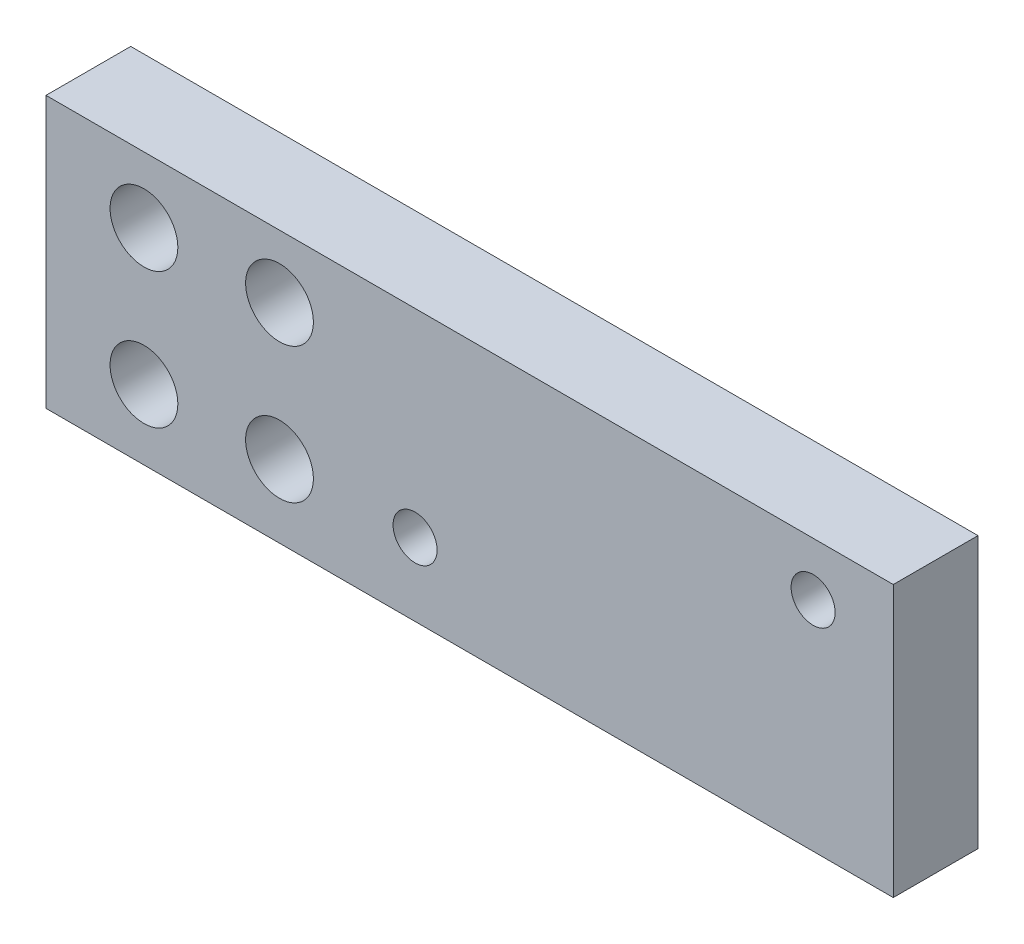
SolidWorks part; units mm, degrees
ref_plane "前基準面" through (0, 0, 0) normal (0, 0, 1) x (1, 0, 0)
ref_plane "上基準面" through (0, 0, 0) normal (0, 1, 0) x (1, 0, 0)
ref_plane "右基準面" through (0, 0, 0) normal (1, 0, 0) x (0, 0, -1)
sketch "草圖1" plane through (0, 0, 0) normal (0, 0, 1) x (1, 0, 0)
  line L5 (-22.7861, 3.8985) -> (27.2139, 3.8985)
  line L6 (-22.7861, 3.8985) -> (-22.7861, -12.1015)
  line L7 (-22.7861, -12.1015) -> (27.2139, -12.1015)
  line L8 (27.2139, 3.8985) -> (27.2139, -12.1015)
  line L9 (2.2139, -12.1015) -> (2.2139, 3.8985) construction
  line L10 (-22.7861, -4.1015) -> (27.2139, -4.1015) construction
  circle A4 centre (-17.006, 0.0173) radius 2
  circle A5 centre (-17.006, -7.9827) radius 2
  circle A6 centre (-9.006, 0.1915) radius 2
  circle A7 centre (-9.006, -7.8085) radius 2
  circle A8 centre (-1.006, -7.8085) radius 1.3
  circle A9 centre (22.4839, 0.7486) radius 1.3
  point P8 (10.6298, -0.8045)
  point P9 (0, 0)
  point P10 (23.9961, 1.2995)
  point P76 (2.2139, -4.1015)
  dimension "D3" = 8
  dimension "D5" = 8
  dimension "D1" = 50
  dimension "D2" = 16
  dimension "D4" = 8
  dimension "D6" = 25
extrude "填料-伸長1" add sketch "草圖1" along normal blind 5 contours L8 L7 L6 L5 | A9 | A5 | A4 | A8 | A7 | A6
